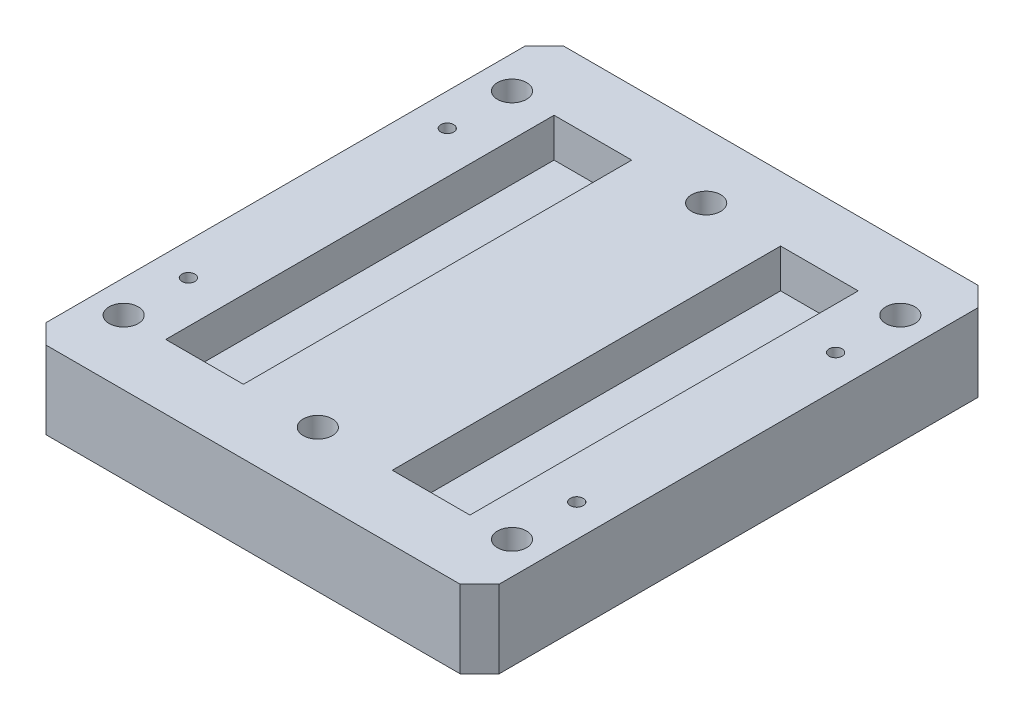
SolidWorks part; units mm, degrees
ref_plane "Plan de face" through (0, 0, 0) normal (0, 0, 1) x (1, 0, 0)
ref_plane "Plan de dessus" through (0, 0, 0) normal (0, 1, 0) x (1, 0, 0)
ref_plane "Plan de droite" through (0, 0, 0) normal (1, 0, 0) x (0, 0, -1)
sketch "Esquisse1" plane through (0, 0, 0) normal (0, 0, 1) x (1, 0, 0)
  line L1 (0, 0) -> (70, 0)
  line L2 (0, 0) -> (0, 12)
  line L3 (0, 12) -> (70, 12)
  line L4 (70, 0) -> (70, 12)
  dimension "D1" = 12
  dimension "D2" = 70
extrude "Boss.-Extru.1" add sketch "Esquisse1" along normal blind 80
sketch "Esquisse2" plane through (0, 0, 80) normal (0, 0, 1) x (1, 0, 0)
  line L0 (35, 0) -> (35, 12) construction
  line L1 (0, 0) -> (70, 0) construction
  line L2 (70, 12) -> (0, 12) construction
  line L3 (58.5, 12) -> (58.5, 6)
  line L4 (23.5, 12) -> (11.5, 12)
  line L5 (23.5, 12) -> (23.5, 6)
  line L6 (23.5, 6) -> (11.5, 6)
  line L7 (11.5, 12) -> (11.5, 6)
  line L8 (46.5, 6) -> (58.5, 6)
  line L9 (46.5, 12) -> (46.5, 6)
  line L10 (46.5, 12) -> (58.5, 12)
  dimension "D1" = 12
  dimension "D2" = 6
  dimension "D3" = 23
extrude "Enlèv. mat.-Extru.1" cut sketch "Esquisse2" against normal through all
sketch "Esquisse4" plane through (0, 12, 0) normal (0, 1, 0) x (1, 0, 0)
  line L0 (0, -10) -> (70, -10) construction
  line L1 (0, -80) -> (0, 0) construction
  line L3 (0, -40) -> (70, -40) construction
  line L4 (70, -80) -> (70, 0) construction
  line L5 (46.5, 0) -> (23.5, 0) construction
  line L6 (0, -70) -> (70, -70) construction
  line L8 (35, -10) -> (35, -70) construction
  circle A0 centre (5, -10) radius 2.25
  circle A1 centre (65, -70) radius 2.25
  circle A2 centre (65, -10) radius 2.25
  circle A3 centre (5, -70) radius 2.25
  circle A4 centre (35, -10) radius 2.25
  circle A5 centre (35, -70) radius 2.25
  dimension "D1" = 4.5
  dimension "D2" = 30
  dimension "D4" = 10
extrude "Enlèv. mat.-Extru.3" cut sketch "Esquisse4" against normal through all
sketch "Esquisse5" plane through (0, 12, 0) normal (0, 1, 0) x (1, 0, 0)
  line L0 (23.5, 0) -> (23.5, -80) construction
  line L1 (11.5, -80) -> (23.5, -80)
  line L2 (11.5, -80) -> (11.5, -70)
  line L3 (11.5, -70) -> (23.5, -70)
  line L4 (23.5, -80) -> (23.5, -70)
  line L5 (35, -80) -> (35, 0) construction
  line L6 (46.5, -80) -> (23.5, -80) construction
  line L7 (46.5, 0) -> (23.5, 0) construction
  line L8 (70, -40) -> (0, -40) construction
  line L9 (70, -80) -> (70, 0) construction
  line L10 (0, -80) -> (0, 0) construction
  line L11 (46.5, -80) -> (46.5, -70)
  line L12 (58.5, -70) -> (46.5, -70)
  line L13 (58.5, -80) -> (58.5, -70)
  line L14 (58.5, -80) -> (46.5, -80)
  line L15 (58.5, 0) -> (46.5, 0)
  line L16 (58.5, 0) -> (58.5, -10)
  line L17 (58.5, -10) -> (46.5, -10)
  line L18 (46.5, 0) -> (46.5, -10)
  line L19 (23.5, 0) -> (23.5, -10)
  line L20 (11.5, -10) -> (23.5, -10)
  line L21 (11.5, 0) -> (11.5, -10)
  line L22 (11.5, 0) -> (23.5, 0)
  dimension "D1" = 10
extrude "Boss.-Extru.2" add sketch "Esquisse5" against normal up to vertex (6 mm away) up to point (46.5, 6, 0)
chamfer "Chanfrein1" distance 3 angle 45 4 edges at (0, 6, 0) (0, 6, 80) (70, 6, 0) (70, 6, 80)
sketch "Esquisse6" plane through (0, 12, 0) normal (0, 1, 0) x (1, 0, 0)
  line L0 (35, -80) -> (35, 0) construction
  line L1 (67, -80) -> (3, -80) construction
  line L2 (67, 0) -> (3, 0) construction
  line L3 (5, -20) -> (35, -20) construction
  line L4 (0, -40) -> (35, -40) construction
  line L5 (0, -77) -> (0, -3) construction
  line L6 (5, -20) -> (5, -40) construction
  line L7 (65, -20) -> (65, -40) construction
  circle A0 centre (5, -20) radius 1
  circle A1 centre (5, -60) radius 1
  circle A2 centre (65, -60) radius 1
  circle A3 centre (65, -20) radius 1
  dimension "D2" = 2
  dimension "D1" = 30
  dimension "D3" = 20
extrude "Enlèv. mat.-Extru.4" cut sketch "Esquisse6" against normal up to vertex (12 mm away) up to point (70, 0, 3)
